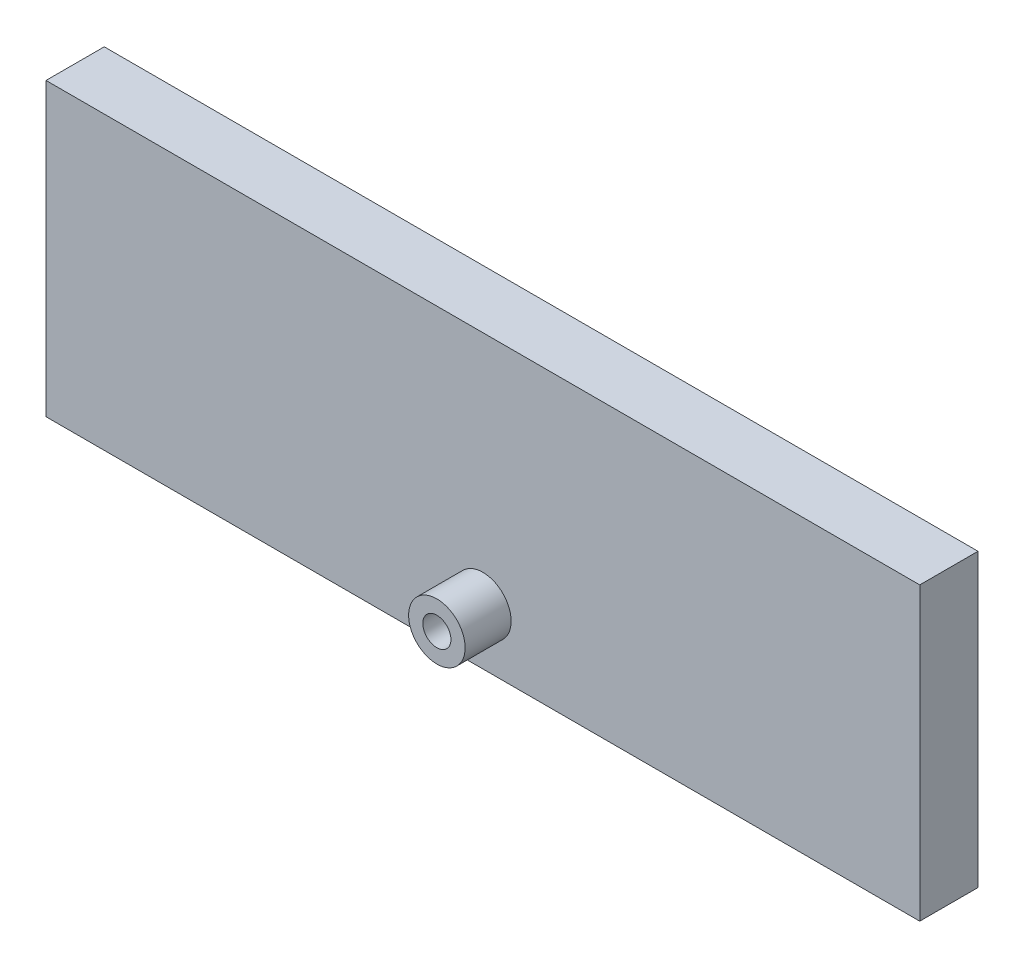
SolidWorks part; units mm, degrees
ref_plane "Front Plane" through (0, 0, 0) normal (0, 0, 1) x (1, 0, 0)
ref_plane "Top Plane" through (0, 0, 0) normal (0, 1, 0) x (1, 0, 0)
ref_plane "Right Plane" through (0, 0, 0) normal (1, 0, 0) x (0, 0, -1)
sketch "Sketch1" plane through (0, 0, 0) normal (0, 0, 1) x (1, 0, 0)
  line L1 (-150, 50) -> (150, 50)
  line L2 (-150, 50) -> (-150, -50)
  line L3 (-150, -50) -> (150, -50)
  line L4 (150, 50) -> (150, -50)
  line L5 (-150, 50) -> (150, -50) construction
  line L6 (-150, -50) -> (150, 50) construction
  point P0 (0, 0)
  dimension "D1" = 100
  dimension "D2" = 300
extrude "Boss-Extrude1" add sketch "Sketch1" along normal blind 20
sketch "Sketch2" plane through (0, 0, 20) normal (0, 0, 1) x (1, 0, 0)
  line L0 (-150, -50) -> (150, -50) construction
  line L1 (150, -50) -> (150, 50) construction
  circle A0 centre (0, -30.95) radius 4.826
  circle A1 centre (0, -30.95) radius 9.7
  dimension "D1" = 19.05
  dimension "D2" = 150
  dimension "D3" = 9.652
  dimension "D4" = 19.4
extrude "Boss-Extrude2" add sketch "Sketch2" along normal blind 15.8
